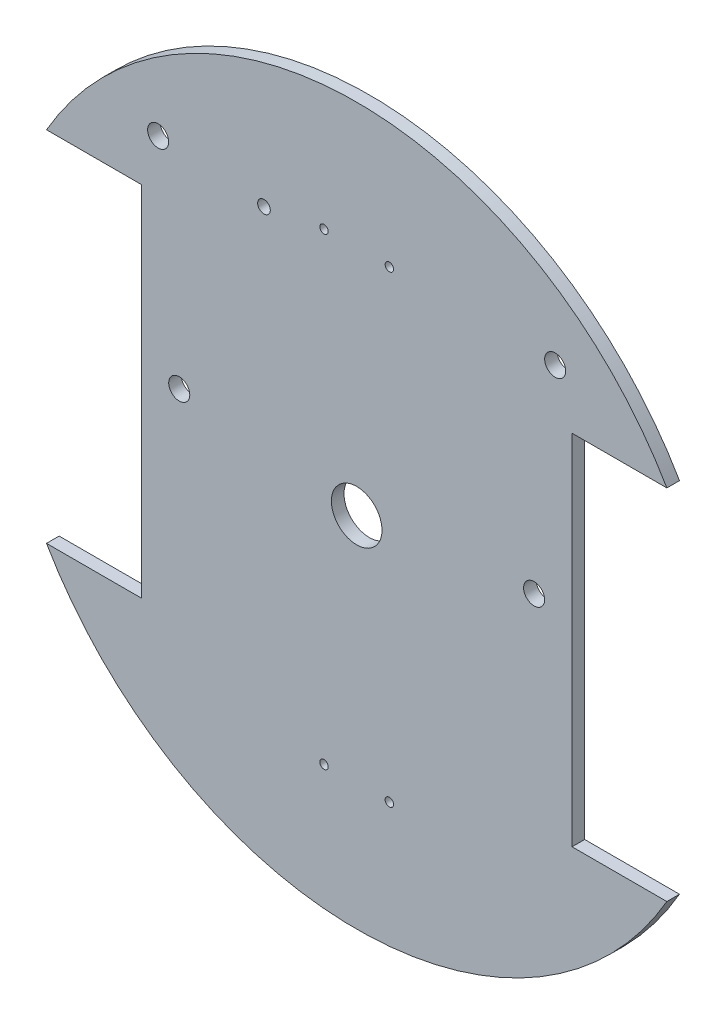
SolidWorks part; units mm, degrees
ref_plane "Plan de face" through (0, 0, 0) normal (0, 0, 1) x (1, 0, 0)
ref_plane "Plan de dessus" through (0, 0, 0) normal (0, 1, 0) x (1, 0, 0)
ref_plane "Plan de droite" through (0, 0, 0) normal (1, 0, 0) x (0, 0, -1)
sketch "Esquisse1" plane through (0, 0, 0) normal (0, 0, 1) x (1, 0, 0)
  circle A0 centre (-147.9597, 62.5489) radius 85
  dimension "D1" = 170
extrude "Boss.-Extru.1" add sketch "Esquisse1" along normal blind 3
sketch "Esquisse2" plane through (0, 0, 0) normal (0, 0, 1) x (1, 0, 0)
  line L0 (-147.9597, 147.5489) -> (-147.9597, -22.4511) construction
  line L1 (-231.5719, 105.0489) -> (-199.0719, 105.0489)
  line L2 (-231.5719, 105.0489) -> (-231.5719, 20.0489)
  line L3 (-231.5719, 20.0489) -> (-199.0719, 20.0489)
  line L4 (-199.0719, 105.0489) -> (-199.0719, 20.0489)
  line L5 (-62.9597, 62.5489) -> (-232.9597, 62.5489) construction
  line L6 (-231.5719, 62.5489) -> (-201.5719, 62.5489) construction
  line L7 (-64.3476, 20.0489) -> (-96.8476, 20.0489)
  line L8 (-64.3476, 105.0489) -> (-64.3476, 20.0489)
  line L9 (-64.3476, 105.0489) -> (-96.8476, 105.0489)
  line L10 (-96.8476, 105.0489) -> (-96.8476, 20.0489)
  circle A0 centre (-147.9597, 62.5489) radius 85 construction
  arc A1 (-221.5719, 105.0489) -> (-221.5719, 20.0489) centre (-147.9597, 62.5489) ccw
  arc A2 (-74.3476, 105.0489) -> (-74.3476, 20.0489) centre (-147.9597, 62.5489) ccw
  dimension "D1" = 85
  dimension "D2" = 32.5
extrude "Enlèv. mat.-Extru.6" cut sketch "Esquisse2" against normal blind 3 from surface at 3 contours L1 A1 L2 L3 L4 | L9 L10 L7 L8 starting at face at (-62.9597, 62.5489, 3)
delete or keep bodies "Corps-Supprimer/Garder 1" type delete bodies bodies 104 103
sketch "Esquisse3" plane through (0, 0, 3) normal (0, 0, 1) x (1, 0, 0)
  line L0 (-147.9597, 147.5489) -> (-147.9597, -22.4511) construction
  line L1 (-199.0719, 62.5489) -> (-96.8476, 62.5489) construction
  line L2 (-199.0719, 20.0489) -> (-199.0719, 105.0489) construction
  line L3 (-96.8476, 20.0489) -> (-96.8476, 105.0489) construction
  line L4 (-147.9597, 62.5489) -> (-96.8476, 62.5489) construction
  line L5 (-158.4597, 117.5489) -> (-137.4597, 117.5489) construction
  arc A1 (-74.3476, 105.0489) -> (-221.5719, 105.0489) centre (-147.9597, 62.5489) ccw construction
  arc A2 (-221.5719, 20.0489) -> (-74.3476, 20.0489) centre (-147.9597, 62.5489) ccw construction
  circle A3 centre (-155.7097, 117.5489) radius 1
  circle A4 centre (-140.2097, 117.5489) radius 1
  circle A5 centre (-140.2097, 7.5489) radius 1
  circle A6 centre (-155.7097, 7.5489) radius 1
  dimension "D3" = 2
  dimension "D4" = 15.5
extrude "Enlèv. mat.-Extru.8" cut sketch "Esquisse3" against normal blind 10 contours A3 | A4 | A6 | A5
sketch "Esquisse53" plane through (0, 0, 0) normal (0, 0, -1) x (-1, 0, 0)
  line L0 (199.0719, 62.5489) -> (96.8476, 62.5489) construction
  line L1 (199.0719, 20.0489) -> (199.0719, 105.0489) construction
  line L2 (96.8476, 20.0489) -> (96.8476, 105.0489) construction
  line L3 (105.8476, 62.5489) -> (105.8476, 22.5155) construction
  line L4 (105.8476, 22.5155) -> (190.0719, 22.5155) construction
  line L5 (190.0719, 22.5155) -> (190.0719, 62.5489) construction
  circle A0 centre (190.0719, 67.5489) radius 2.5
  circle A1 centre (105.8476, 67.5489) radius 2.5
  dimension "D3" = 0
  dimension "D1" = 9
  dimension "D2" = 9
  dimension "D4" = 5
  dimension "D5" = 5
extrude "Enlèv. mat.-Extru.21" cut sketch "Esquisse53" against normal blind 10
sketch "Esquisse54" plane through (0, 0, 0) normal (0, 0, -1) x (-1, 0, 0)
  line L0 (195.0719, 133.2981) -> (195.0719, 14.2319) construction
  line L1 (199.0719, 20.0489) -> (199.0719, 105.0489) construction
  line L2 (213.1882, 117.0489) -> (82.7313, 117.0489) construction
  line L3 (199.0719, 105.0489) -> (221.5719, 105.0489) construction
  line L4 (147.9597, 147.5489) -> (147.9597, -22.4511) construction
  arc A0 (221.5719, 105.0489) -> (74.3476, 105.0489) centre (147.9597, 62.5489) ccw construction
  circle A1 centre (195.0719, 117.0489) radius 2.5
  arc A2 (74.3476, 20.0489) -> (221.5719, 20.0489) centre (147.9597, 62.5489) ccw construction
  circle A3 centre (100.8476, 117.0489) radius 2.5
  dimension "D1" = 4
  dimension "D2" = 12
extrude "Enlèv. mat.-Extru.22" cut sketch "Esquisse54" against normal blind 10
sketch "Esquisse55" plane through (0, 0, 0) normal (0, 0, -1) x (-1, 0, 0)
  line L0 (214.8085, 115.0489) -> (81.111, 115.0489) construction
  line L1 (147.9597, 147.5489) -> (147.9597, -22.4511) construction
  line L2 (199.0719, 105.0489) -> (221.5719, 105.0489) construction
  arc A0 (221.5719, 105.0489) -> (74.3476, 105.0489) centre (147.9597, 62.5489) ccw construction
  circle A1 centre (169.9597, 115.0489) radius 1.5
  arc A2 (74.3476, 20.0489) -> (221.5719, 20.0489) centre (147.9597, 62.5489) ccw construction
  dimension "D1" = 22
  dimension "D2" = 10
extrude "Enlèv. mat.-Extru.23" cut sketch "Esquisse55" against normal blind 10
sketch "Esquisse56" plane through (0, 0, 0) normal (0, 0, -1) x (-1, 0, 0)
  line L0 (147.9597, 147.5489) -> (147.9597, -22.4511) construction
  line L1 (147.9597, -22.4511) -> (199.0719, 62.5489) construction
  line L2 (199.0719, 20.0489) -> (199.0719, 105.0489) construction
  line L3 (199.0719, 62.5489) -> (96.8476, 62.5489) construction
  line L4 (96.8476, 20.0489) -> (96.8476, 105.0489) construction
  arc A0 (221.5719, 105.0489) -> (74.3476, 105.0489) centre (147.9597, 62.5489) ccw construction
  arc A1 (74.3476, 20.0489) -> (221.5719, 20.0489) centre (147.9597, 62.5489) ccw construction
  circle A2 centre (147.9597, 62.5489) radius 6
extrude "Enlèv. mat.-Extru.24" cut sketch "Esquisse56" against normal blind 10
